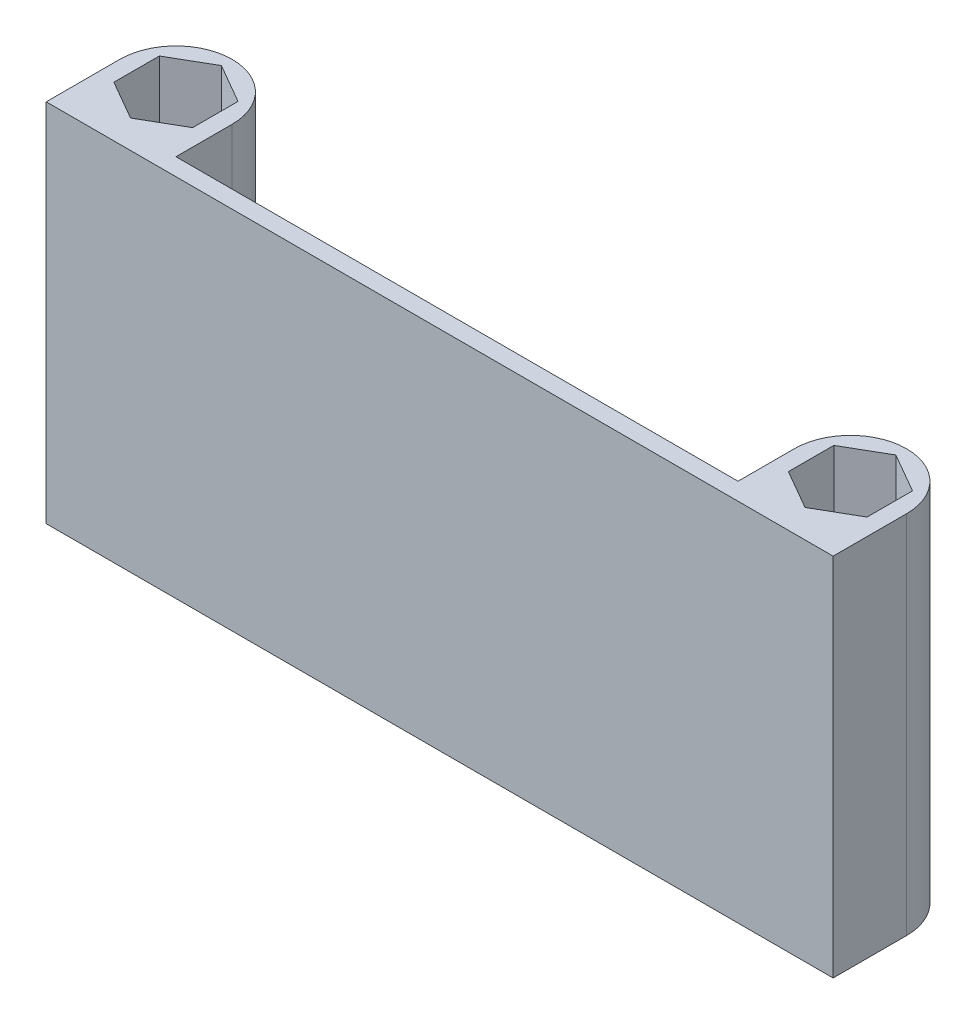
SolidWorks part; units mm, degrees
ref_plane "Front Plane" through (0, 0, 0) normal (0, 0, 1) x (1, 0, 0)
ref_plane "Top Plane" through (0, 0, 0) normal (0, 1, 0) x (1, 0, 0)
ref_plane "Right Plane" through (0, 0, 0) normal (1, 0, 0) x (0, 0, -1)
sketch "Sketch1" plane through (0, 0, 0) normal (0, 1, 0) x (1, 0, 0)
  line L0 (0, 0) -> (-24, 0) construction
  line L1 (-24, -3.2332) -> (-21.2, -1.6166)
  line L2 (-21.2, -1.6166) -> (-21.2, 1.6166)
  line L3 (-21.2, 1.6166) -> (-24, 3.2332)
  line L4 (-24, 3.2332) -> (-26.8, 1.6166)
  line L5 (-26.8, 1.6166) -> (-26.8, -1.6166)
  line L6 (-26.8, -1.6166) -> (-24, -3.2332)
  line L7 (0, 0) -> (24, 0) construction
  line L8 (-24, 3.2332) -> (-24, -3.2332) construction
  line L9 (24, -3.2332) -> (26.8, -1.6166)
  line L10 (26.8, -1.6166) -> (26.8, 1.6166)
  line L11 (26.8, 1.6166) -> (24, 3.2332)
  line L12 (24, 3.2332) -> (21.2, 1.6166)
  line L13 (21.2, 1.6166) -> (21.2, -1.6166)
  line L14 (21.2, -1.6166) -> (24, -3.2332)
  line L15 (-28, 0) -> (-28, -5.2332)
  line L16 (-28, -5.2332) -> (28, -5.2332)
  line L17 (28, -5.2332) -> (28, 0)
  line L18 (-20, 0) -> (-20, -4)
  line L19 (-20, -4) -> (20, -4)
  line L20 (20, 0) -> (20, -4)
  circle A0 centre (-24, 0) radius 2.8 construction
  circle A1 centre (24, 0) radius 2.8 construction
  arc A2 (-20, 0) -> (-28, 0) centre (-24, 0) ccw
  arc A3 (28, 0) -> (20, 0) centre (24, 0) ccw
  dimension "D3" = 8
  dimension "D1" = 5.6
  dimension "D2" = 42.4
  dimension "D4" = 2
extrude "Boss-Extrude1" add sketch "Sketch1" along normal blind 26
sketch "Sketch2" plane through (0, 0, 4) normal (0, 0, -1) x (-1, 0, 0)
  line L0 (-20, 3) -> (20, 3) construction
  line L1 (-20, 26) -> (-20, 0) construction
  line L2 (20, 26) -> (20, 0) construction
  line L3 (-20, 0) -> (20, 0) construction
  text T0 " B1" font "Impact" height 20
  dimension "D1" = 3
extrude "Boss-Extrude2" add sketch "Sketch2" along normal blind 2
sketch "Sketch3" [suppressed] plane through (0, 0, 4) normal (0, 0, -1) x (-1, 0, 0)
  line L0 (-20, 3) -> (20, 3) construction
  line L1 (-20, 26) -> (-20, 0) construction
  line L2 (20, 26) -> (20, 0) construction
  line L3 (-20, 0) -> (20, 0) construction
  text T0 " B2" font "Impact" height 20
  dimension "D1" = 3
extrude "Boss-Extrude3" [suppressed] add sketch "Sketch3" along normal blind 2
sketch "Sketch4" [suppressed] plane through (0, 0, 4) normal (0, 0, -1) x (-1, 0, 0)
  line L0 (-20, 3) -> (20, 3) construction
  line L1 (-20, 26) -> (-20, 0) construction
  line L2 (20, 26) -> (20, 0) construction
  line L3 (-20, 0) -> (20, 0) construction
  text T0 " B3" font "Impact" height 20
  dimension "D1" = 3
extrude "Boss-Extrude4" [suppressed] add sketch "Sketch4" along normal blind 2
sketch "Sketch5" [suppressed] plane through (0, 0, 4) normal (0, 0, -1) x (-1, 0, 0)
  line L0 (-20, 3) -> (20, 3) construction
  line L1 (-20, 26) -> (-20, 0) construction
  line L2 (20, 26) -> (20, 0) construction
  line L3 (-20, 0) -> (20, 0) construction
  text T0 " B4" font "Impact" height 20
  dimension "D1" = 3
extrude "Boss-Extrude5" [suppressed] add sketch "Sketch5" along normal blind 2
sketch "Sketch6" [suppressed] plane through (0, 0, 4) normal (0, 0, -1) x (-1, 0, 0)
  line L0 (-20, 3) -> (20, 3) construction
  line L1 (-20, 26) -> (-20, 0) construction
  line L2 (20, 26) -> (20, 0) construction
  line L3 (-20, 0) -> (20, 0) construction
  text T0 " B5" font "Impact" height 20
  dimension "D1" = 3
extrude "Boss-Extrude6" [suppressed] add sketch "Sketch6" along normal blind 2
sketch "Sketch7" [suppressed] plane through (0, 0, 4) normal (0, 0, -1) x (-1, 0, 0)
  line L0 (-20, 3) -> (20, 3) construction
  line L1 (-20, 26) -> (-20, 0) construction
  line L2 (20, 26) -> (20, 0) construction
  line L3 (-20, 0) -> (20, 0) construction
  text T0 " B6" font "Impact" height 20
  dimension "D1" = 3
extrude "Boss-Extrude7" [suppressed] add sketch "Sketch7" along normal blind 2
sketch "Sketch8" [suppressed] plane through (0, 0, 4) normal (0, 0, -1) x (-1, 0, 0)
  line L0 (-20, 3) -> (20, 3) construction
  line L1 (-20, 26) -> (-20, 0) construction
  line L2 (20, 26) -> (20, 0) construction
  line L3 (-20, 0) -> (20, 0) construction
  text T0 " W1" font "Impact" height 20
  dimension "D1" = 3
extrude "Boss-Extrude8" [suppressed] add sketch "Sketch8" along normal blind 2
sketch "Sketch9" [suppressed] plane through (0, 0, 4) normal (0, 0, -1) x (-1, 0, 0)
  line L0 (-20, 3) -> (20, 3) construction
  line L1 (-20, 26) -> (-20, 0) construction
  line L2 (20, 26) -> (20, 0) construction
  line L3 (-20, 0) -> (20, 0) construction
  text T0 " W2" font "Impact" height 20
  dimension "D1" = 3
extrude "Boss-Extrude9" [suppressed] add sketch "Sketch9" along normal blind 2
